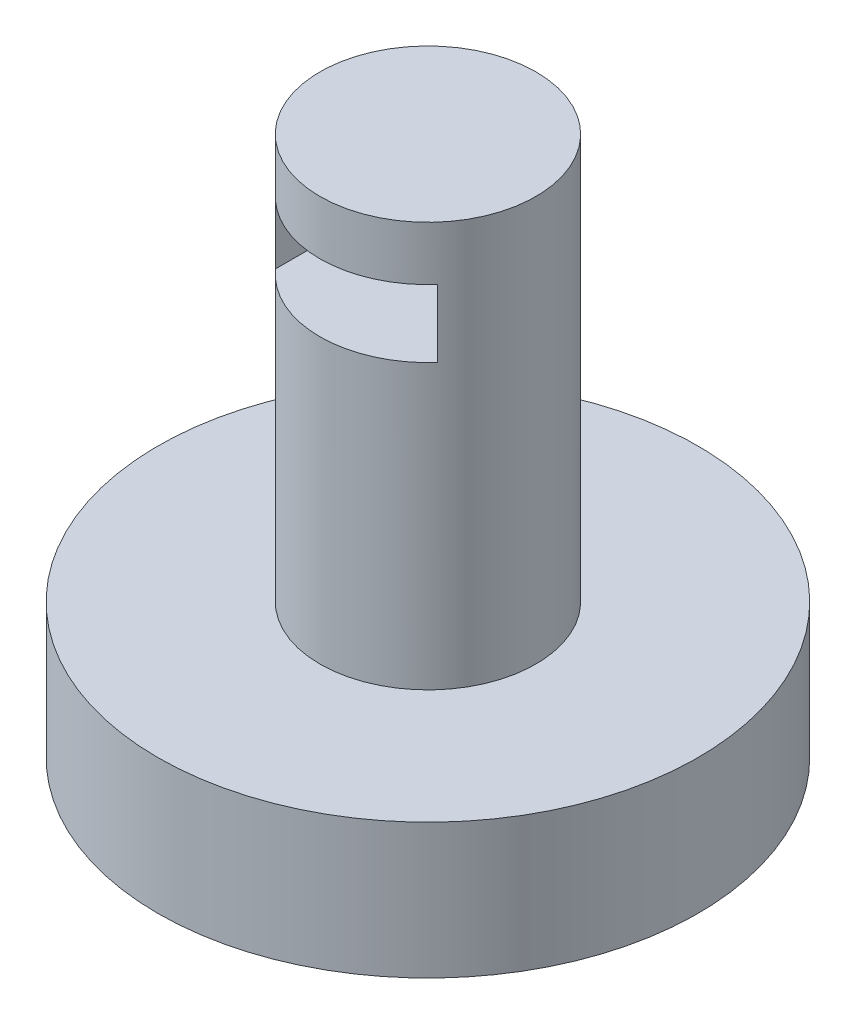
SolidWorks part; units mm, degrees
ref_plane "Front Plane" through (0, 0, 0) normal (0, 0, 1) x (1, 0, 0)
ref_plane "Top Plane" through (0, 0, 0) normal (0, 1, 0) x (1, 0, 0)
ref_plane "Right Plane" through (0, 0, 0) normal (1, 0, 0) x (0, 0, -1)
sketch "Sketch2" plane through (0, 0, 0) normal (0, 1, 0) x (1, 0, 0)
  circle A0 centre (0, 0) radius 20
  dimension "D1" = 40
extrude "Boss-Extrude1" add sketch "Sketch2" along normal blind 10
sketch "Sketch3" plane through (0, 10, 0) normal (0, 1, 0) x (1, 0, 0)
  circle A0 centre (0, 0) radius 8
  dimension "D1" = 16
extrude "Boss-Extrude2" add sketch "Sketch3" along normal blind 30
sketch "Sketch4" plane through (0, 0, 0) normal (0, 0, 1) x (1, 0, 0)
  line L2 (-8, 40) -> (-8, 10) construction
  line L3 (-6, 36) -> (6, 36)
  line L4 (-6, 36) -> (-6, 31)
  line L5 (-6, 31) -> (6, 31)
  line L6 (6, 36) -> (6, 31)
  line L7 (-6, 36) -> (-8, 36) construction
  line L8 (6, 36) -> (8, 36) construction
  line L9 (8, 10) -> (8, 40) construction
  line L10 (8, 40) -> (-8, 40) construction
  dimension "D1" = 4
  dimension "D2" = 5
  dimension "D3" = 12
extrude "Cut-Extrude1" cut sketch "Sketch4" along normal through all both and the other way through all
sketch "Sketch5" plane through (0, 0, 0) normal (0, -1, 0) x (1, 0, 0)
  circle A0 centre (0, 0) radius 4
  dimension "D1" = 8
extrude "Cut-Extrude2" cut sketch "Sketch5" against normal blind 3 contours A0
